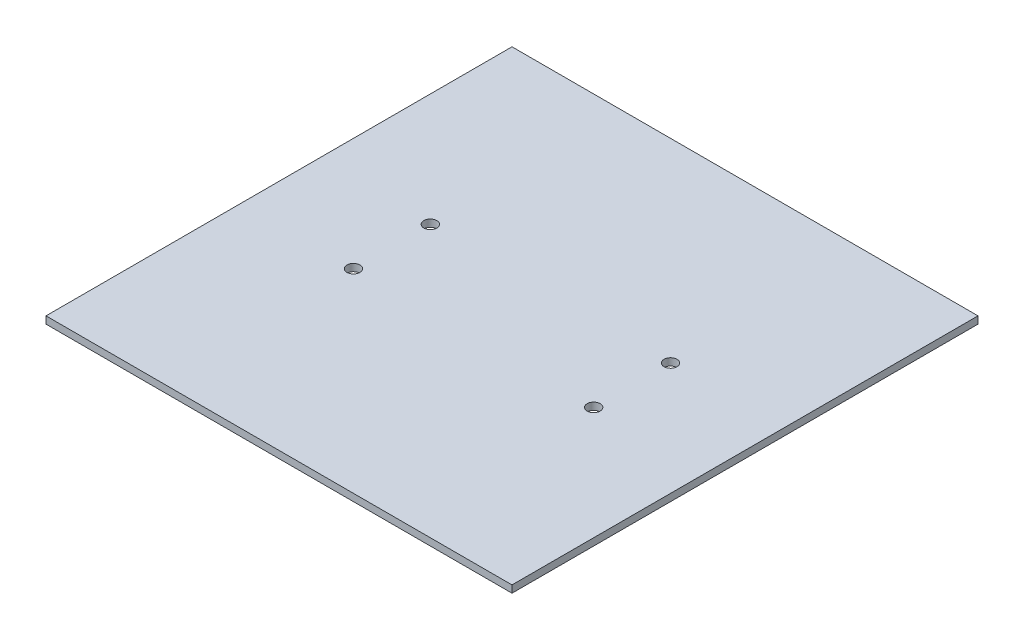
SolidWorks part; units mm, degrees
ref_plane "前视基准面" through (0, 0, 0) normal (0, 0, 1) x (1, 0, 0)
ref_plane "上视基准面" through (0, 0, 0) normal (0, 1, 0) x (1, 0, 0)
ref_plane "右视基准面" through (0, 0, 0) normal (1, 0, 0) x (0, 0, -1)
sketch "草图1" plane through (0, 0, 0) normal (0, 1, 0) x (1, 0, 0)
  line L0 (-97, 97) -> (97, 97)
  line L1 (-97, -97) -> (97, -97)
  line L2 (-97, 97) -> (-97, -97)
  line L3 (97, 97) -> (97, -97)
  circle A7 centre (50, 16) radius 2.695
  circle A8 centre (50, -16) radius 2.695
  circle A9 centre (-50, -16) radius 2.695
  circle A10 centre (-50, 16) radius 2.695
  dimension "D3" = 32
  dimension "D1" = 97
  dimension "D2" = 50
  dimension "D4" = 50
  dimension "D5" = 50
  dimension "D6" = 32
  dimension "D7" = 16
  dimension "D8" = 16
  dimension "D10" = 97
extrude "凸台-拉伸1" add sketch "草图1" along normal blind 3
